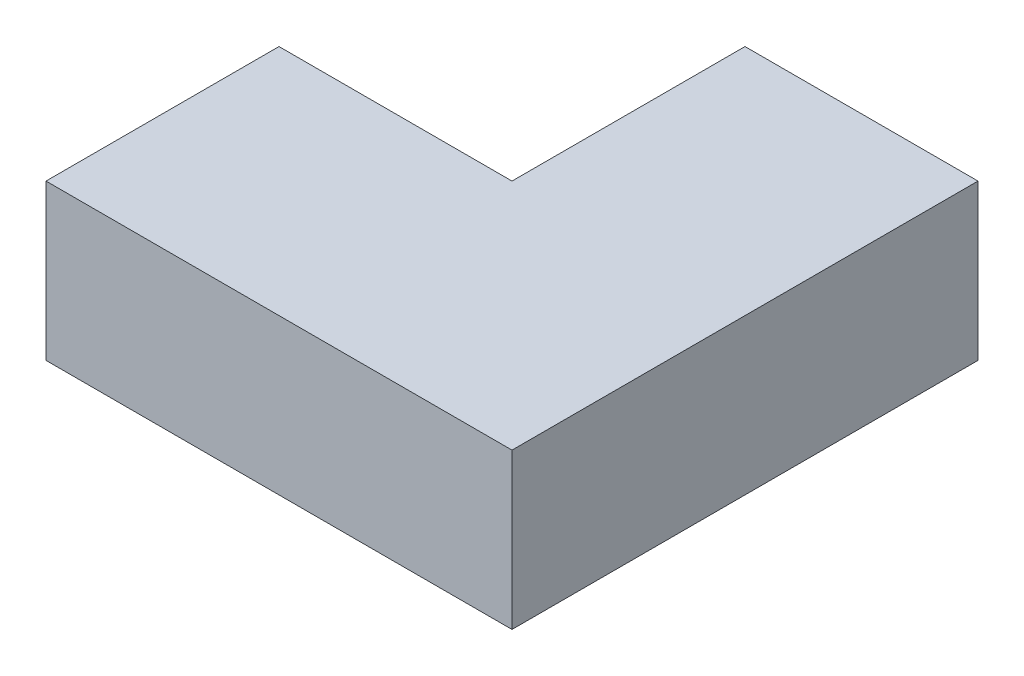
SolidWorks part; units mm, degrees
ref_plane "Alzado" through (0, 0, 0) normal (0, 0, 1) x (1, 0, 0)
ref_plane "Planta" through (0, 0, 0) normal (0, 1, 0) x (1, 0, 0)
ref_plane "Vista lateral" through (0, 0, 0) normal (1, 0, 0) x (0, 0, -1)
sketch "Croquis1" plane through (0, 0, 0) normal (0, 1, 0) x (1, 0, 0)
  line L0 (0, 0) -> (0, 2.5)
  line L1 (0, 2.5) -> (4.5, 2.5)
  line L2 (4.5, 2.5) -> (4.5, 7)
  line L3 (4.5, 7) -> (7, 7)
  line L4 (7, 7) -> (7, 0)
  line L5 (7, 0) -> (0, 0)
  point P7 (2.25, 2.5)
  point P8 (6.6159, 0)
  dimension "D1" = 2.5
  dimension "D2" = 7
extrude "Saliente-Extruir1" add sketch "Croquis1" along normal blind 0.5
sketch "Croquis2" plane through (0, 0.5, 0) normal (0, 1, 0) x (1, 0, 0)
  line L0 (0, 2.5) -> (0, 0) construction
  line L1 (7, 7) -> (4.5, 7) construction
  line L2 (4.5, 7) -> (4.5, 2.5) construction
  line L3 (4.5, 2.5) -> (0, 2.5) construction
  line L4 (0, 2.5) -> (0, 0)
  line L5 (7, 7) -> (4.5, 7)
  line L6 (4.5, 7) -> (4.5, 2.5)
  line L7 (4.5, 2.5) -> (0, 2.5)
  line L8 (0, 0) -> (0, -2)
  line L9 (0, -2) -> (9, -2)
  line L10 (9, -2) -> (9, 7)
  line L11 (9, 7) -> (7, 7)
  dimension "D1" = 9
extrude "Saliente-Extruir2" add sketch "Croquis2" along normal blind 3
